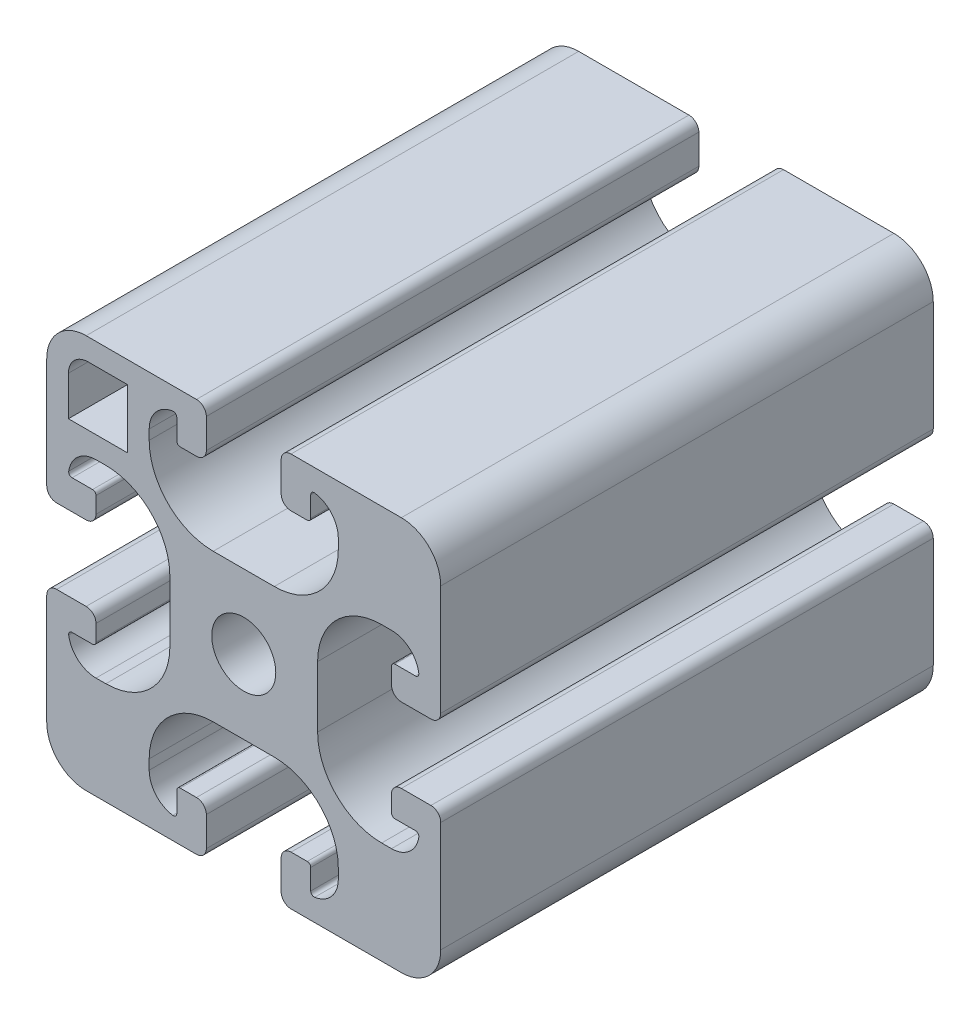
SolidWorks part; units mm, degrees
material "6061 Alaşım"
ref_plane "Ön Düzlem" through (0, 0, 0) normal (0, 0, 1) x (1, 0, 0)
ref_plane "Üst Düzlem" through (0, 0, 0) normal (0, 1, 0) x (1, 0, 0)
ref_plane "Sağ Düzlem" through (0, 0, 0) normal (1, 0, 0) x (0, 0, -1)
sketch "Çizim1" plane through (0, 0, 0) normal (0, 0, 1) x (1, 0, 0)
  line L0 (-6.45, 15) -> (-4.8, 15)
  line L5 (-20, -20) -> (20, -20) construction
  line L6 (-20, -20) -> (-20, 20) construction
  line L7 (-20, 20) -> (20, 20) construction
  line L8 (20, -20) -> (20, 20) construction
  line L9 (-20, -20) -> (20, 20) construction
  line L10 (-20, 20) -> (20, -20) construction
  line L11 (-3.8, 16) -> (-3.8, 19)
  line L12 (-6.8, 15.35) -> (-6.8, 17.4249)
  line L13 (-9.6, 15) -> (-9.6, 14)
  line L14 (0, 0) -> (0, 20) construction
  line L15 (0, 7.5) -> (-3.1, 7.5)
  line L16 (-6.8, 17.8) -> (-4.8893, 17.8) construction
  line L17 (-11.8, 11.8) -> (-11.8, 17.8)
  line L18 (-11.8, 17.8) -> (-15.8, 17.8)
  line L19 (-17.8, 17.8) -> (-20, 20) construction
  line L20 (-16, 20) -> (-4.8, 20)
  line L21 (0, 7.5) -> (0, 3.25)
  line L23 (-7.5, 0) -> (-3.25, 0)
  line L24 (-7.5, 0) -> (-7.5, 3.1)
  line L25 (-15, 9.6) -> (-14, 9.6)
  line L26 (-15.35, 6.8) -> (-17.4249, 6.8)
  line L27 (-15, 6.45) -> (-15, 4.8)
  line L28 (-16, 3.8) -> (-19, 3.8)
  line L29 (-20, 16) -> (-20, 4.8)
  line L30 (-17.8, 11.8) -> (-17.8, 15.8)
  line L31 (-11.8, 11.8) -> (-17.8, 11.8)
  line L32 (16, 20) -> (4.8, 20)
  line L33 (3.8, 16) -> (3.8, 19)
  line L34 (6.45, 15) -> (4.8, 15)
  line L35 (6.8, 15.35) -> (6.8, 17.4249)
  line L36 (9.6, 15) -> (9.6, 14)
  line L37 (0, 7.5) -> (3.1, 7.5)
  line L38 (0, 7.5) -> (0, 3.25)
  line L39 (7.5, 0) -> (3.25, 0)
  line L40 (7.5, 0) -> (7.5, 3.1)
  line L41 (15, 9.6) -> (14, 9.6)
  line L42 (15.35, 6.8) -> (17.4249, 6.8)
  line L43 (15, 6.45) -> (15, 4.8)
  line L44 (16, 3.8) -> (19, 3.8)
  line L45 (20, 16) -> (20, 4.8)
  line L46 (20, -16) -> (20, -4.8)
  line L47 (16, -3.8) -> (19, -3.8)
  line L48 (15, -6.45) -> (15, -4.8)
  line L49 (15.35, -6.8) -> (17.4249, -6.8)
  line L50 (15, -9.6) -> (14, -9.6)
  line L51 (7.5, 0) -> (7.5, -3.1)
  line L52 (7.5, 0) -> (3.25, 0)
  line L53 (0, -7.5) -> (0, -3.25)
  line L54 (0, -7.5) -> (3.1, -7.5)
  line L55 (9.6, -15) -> (9.6, -14)
  line L56 (6.8, -15.35) -> (6.8, -17.4249)
  line L57 (6.45, -15) -> (4.8, -15)
  line L58 (3.8, -16) -> (3.8, -19)
  line L59 (16, -20) -> (4.8, -20)
  line L60 (-16, -20) -> (-4.8, -20)
  line L61 (-3.8, -16) -> (-3.8, -19)
  line L62 (-6.45, -15) -> (-4.8, -15)
  line L63 (-6.8, -15.35) -> (-6.8, -17.4249)
  line L64 (-9.6, -15) -> (-9.6, -14)
  line L65 (0, -7.5) -> (-3.1, -7.5)
  line L66 (0, -7.5) -> (0, -3.25)
  line L67 (-7.5, 0) -> (-3.25, 0)
  line L68 (-7.5, 0) -> (-7.5, -3.1)
  line L69 (-15, -9.6) -> (-14, -9.6)
  line L70 (-15.35, -6.8) -> (-17.4249, -6.8)
  line L71 (-15, -6.45) -> (-15, -4.8)
  line L72 (-16, -3.8) -> (-19, -3.8)
  line L73 (-20, -16) -> (-20, -4.8)
  circle A0 centre (0, 0) radius 3.25 construction
  arc A1 (-7.2, 17.7713) -> (-9.6, 15) centre (-6.8, 15) ccw
  arc A2 (-9.6, 14) -> (-3.1, 7.5) centre (-3.1, 14) ccw
  arc A3 (-3.25, 0) -> (0, 3.25) centre (0, 0) cw
  arc A4 (-3.8, 19) -> (-4.8, 20) centre (-4.8, 19) ccw
  arc A5 (-4.8, 15) -> (-3.8, 16) centre (-4.8, 16) ccw
  arc A6 (-6.8, 17.4249) -> (-7.2, 17.7713) centre (-7.15, 17.4249) ccw
  arc A7 (-6.45, 15) -> (-6.8, 15.35) centre (-6.45, 15.35) cw
  arc A8 (-14, 9.6) -> (-7.5, 3.1) centre (-14, 3.1) cw
  arc A9 (-17.7713, 7.2) -> (-15, 9.6) centre (-15, 6.8) cw
  arc A10 (-17.4249, 6.8) -> (-17.7713, 7.2) centre (-17.4249, 7.15) cw
  arc A11 (-15, 6.45) -> (-15.35, 6.8) centre (-15.35, 6.45) ccw
  arc A12 (-15, 4.8) -> (-16, 3.8) centre (-16, 4.8) cw
  arc A13 (-19, 3.8) -> (-20, 4.8) centre (-19, 4.8) cw
  arc A14 (-20, 16) -> (-16, 20) centre (-16, 16) cw
  arc A15 (-15.8, 17.8) -> (-17.8, 15.8) centre (-15.8, 15.8) ccw
  arc A16 (16, 20) -> (20, 16) centre (16, 16) cw
  arc A17 (3.8, 19) -> (4.8, 20) centre (4.8, 19) cw
  arc A18 (4.8, 15) -> (3.8, 16) centre (4.8, 16) cw
  arc A19 (6.45, 15) -> (6.8, 15.35) centre (6.45, 15.35) ccw
  arc A20 (6.8, 17.4249) -> (7.2, 17.7713) centre (7.15, 17.4249) cw
  arc A21 (7.2, 17.7713) -> (9.6, 15) centre (6.8, 15) cw
  arc A22 (9.6, 14) -> (3.1, 7.5) centre (3.1, 14) cw
  arc A23 (0, 3.25) -> (3.25, 0) centre (0, 0) cw
  arc A24 (14, 9.6) -> (7.5, 3.1) centre (14, 3.1) ccw
  arc A25 (17.7713, 7.2) -> (15, 9.6) centre (15, 6.8) ccw
  arc A26 (17.4249, 6.8) -> (17.7713, 7.2) centre (17.4249, 7.15) ccw
  arc A27 (15, 6.45) -> (15.35, 6.8) centre (15.35, 6.45) cw
  arc A28 (15, 4.8) -> (16, 3.8) centre (16, 4.8) ccw
  arc A29 (19, 3.8) -> (20, 4.8) centre (19, 4.8) ccw
  arc A30 (20, -16) -> (16, -20) centre (16, -16) cw
  arc A31 (19, -3.8) -> (20, -4.8) centre (19, -4.8) cw
  arc A32 (15, -4.8) -> (16, -3.8) centre (16, -4.8) cw
  arc A33 (15, -6.45) -> (15.35, -6.8) centre (15.35, -6.45) ccw
  arc A34 (17.4249, -6.8) -> (17.7713, -7.2) centre (17.4249, -7.15) cw
  arc A35 (17.7713, -7.2) -> (15, -9.6) centre (15, -6.8) cw
  arc A36 (14, -9.6) -> (7.5, -3.1) centre (14, -3.1) cw
  arc A37 (3.25, 0) -> (0, -3.25) centre (0, 0) cw
  arc A38 (9.6, -14) -> (3.1, -7.5) centre (3.1, -14) ccw
  arc A39 (7.2, -17.7713) -> (9.6, -15) centre (6.8, -15) ccw
  arc A40 (6.8, -17.4249) -> (7.2, -17.7713) centre (7.15, -17.4249) ccw
  arc A41 (6.45, -15) -> (6.8, -15.35) centre (6.45, -15.35) cw
  arc A42 (4.8, -15) -> (3.8, -16) centre (4.8, -16) ccw
  arc A43 (3.8, -19) -> (4.8, -20) centre (4.8, -19) ccw
  arc A44 (-16, -20) -> (-20, -16) centre (-16, -16) cw
  arc A45 (-3.8, -19) -> (-4.8, -20) centre (-4.8, -19) cw
  arc A46 (-4.8, -15) -> (-3.8, -16) centre (-4.8, -16) cw
  arc A47 (-6.45, -15) -> (-6.8, -15.35) centre (-6.45, -15.35) ccw
  arc A48 (-6.8, -17.4249) -> (-7.2, -17.7713) centre (-7.15, -17.4249) cw
  arc A49 (-7.2, -17.7713) -> (-9.6, -15) centre (-6.8, -15) cw
  arc A50 (-9.6, -14) -> (-3.1, -7.5) centre (-3.1, -14) cw
  arc A51 (0, -3.25) -> (-3.25, 0) centre (0, 0) cw
  arc A52 (-14, -9.6) -> (-7.5, -3.1) centre (-14, -3.1) ccw
  arc A53 (-17.7713, -7.2) -> (-15, -9.6) centre (-15, -6.8) ccw
  arc A54 (-17.4249, -6.8) -> (-17.7713, -7.2) centre (-17.4249, -7.15) ccw
  arc A55 (-15, -6.45) -> (-15.35, -6.8) centre (-15.35, -6.45) cw
  arc A56 (-15, -4.8) -> (-16, -3.8) centre (-16, -4.8) ccw
  arc A57 (-19, -3.8) -> (-20, -4.8) centre (-19, -4.8) ccw
  point P0 (0, 0)
  point P28 (-3.8, 20)
  point P36 (-6.8, 15)
  point P188 (0, 0)
  dimension "D3" = 6.5
  dimension "D8" = 5
  dimension "D9" = 6.5
  dimension "D12" = 1
  dimension "D13" = 0.35
  dimension "D14" = 4
  dimension "D15" = 2
  dimension "D1" = 40
  dimension "D2" = 40
  dimension "D4" = 3.8
  dimension "D5" = 3
  dimension "D6" = 12.5
  dimension "D7" = 2.8
  dimension "D10" = 5
  dimension "D11" = 2.2
  dimension "D16" = 4
extrude "Yükseklik-Ekstrüzyon1" add sketch "Çizim1" against normal blind 50 contours A14 L29 A13 L28 A12 L27 A11 L26 A10 A9 L25 A8 L24 L23 A3 L21 L15 A2 L13 A1 A6 L12 A7 L0 A5 L11 A4 L20 A15 L18 L17 L31 L30 | L44 A29 L45 A16 L32 A17 L33 A18 L34 A19 L35 A20 A21 L36 A22 L37 L21 A23 L39 L40 A24 L41 A25 A26 L42 A27 L43 A28 | L58 A43 L59 A30 L46 A31 L47 A32 L48 A33 L49 A34 A35 L50 A36 L51 L39 A37 L53 L54 A38 L55 A39 A40 L56 A41 L57 A42 | L72 A57 L73 A44 L60 A45 L61 A46 L62 A47 L63 A48 A49 L64 A50 L65 L53 A51 L23 L68 A52 L69 A53 A54 L70 A55 L71 A56
